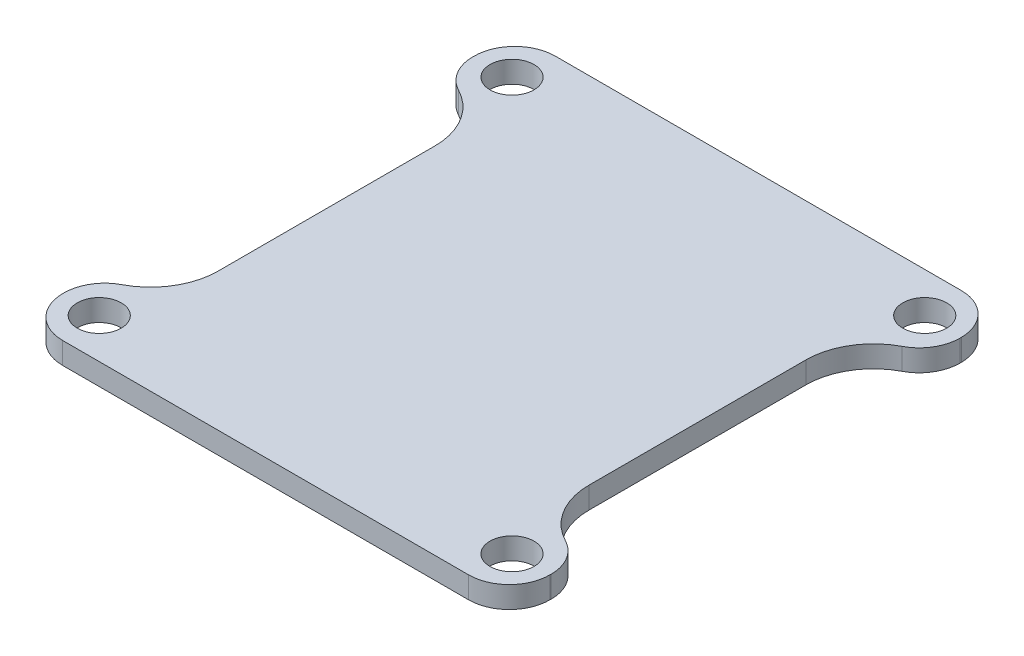
SolidWorks part; units mm, degrees
ref_plane "Front Plane" through (0, 0, 0) normal (0, 0, 1) x (1, 0, 0)
ref_plane "Top Plane" through (0, 0, 0) normal (0, 1, 0) x (1, 0, 0)
ref_plane "Right Plane" through (0, 0, 0) normal (1, 0, 0) x (0, 0, -1)
sketch "Sketch1" plane through (0, 0, 0) normal (0, 1, 0) x (1, 0, 0)
  line L0 (0, 18.2) -> (0, -18.2) construction
  line L1 (-18, 18.2) -> (18, 18.2)
  line L2 (-18, 18.2) -> (-18, -18.2)
  line L3 (-18, -18.2) -> (18, -18.2)
  line L4 (18, 18.2) -> (18, -18.2)
  line L5 (-18, 18.2) -> (18, -18.2) construction
  line L6 (-18, -18.2) -> (18, 18.2) construction
  line L7 (13.7, 18.2) -> (-13.7, 18.2)
  line L8 (13.7, 18.2) -> (13.7, -18.2)
  line L9 (13.7, -18.2) -> (-13.7, -18.2)
  line L10 (-13.7, 18.2) -> (-13.7, -18.2)
  line L11 (13.7, 18.2) -> (-13.7, -18.2) construction
  line L12 (13.7, -18.2) -> (-13.7, 18.2) construction
  line L13 (-18, 0) -> (18, 0) construction
  line L15 (18, 12.1) -> (-18, 12.1)
  line L16 (18, 12.1) -> (18, -12.1)
  line L17 (18, -12.1) -> (-18, -12.1)
  line L18 (-18, 12.1) -> (-18, -12.1)
  line L19 (18, 12.1) -> (-18, -12.1) construction
  line L20 (18, -12.1) -> (-18, 12.1) construction
  circle A0 centre (-15.25, 15.25) radius 1.625
  circle A1 centre (15.25, 15.25) radius 1.625
  circle A2 centre (15.25, -15.25) radius 1.625
  circle A3 centre (-15.25, -15.25) radius 1.625
  point P0 (0, 0)
  point P5 (0, 0)
  point P23 (0, 0)
  point P28 (0, 0)
  dimension "D4" = 3.25
  dimension "D1" = 36.4
  dimension "D2" = 36
  dimension "D3" = 27.4
  dimension "D5" = 30.5
  dimension "D6" = 30.5
  dimension "D7" = 24.2
extrude "Boss-Extrude1" add sketch "Sketch1" along normal blind 1.6 contours L15 L8 L1 L10 | L17 L8 L15 L10 | L4 L17 L8 L3 A2 | L8 L17 L10 L3 | L10 L17 L2 L3 A3 | L15 L4 L1 L8 A1 | L15 L10 L1 L2 A0
fillet "Fillet1" radius 3 8 edges at (-18, 0.8, 12.1) (-18, 0.8, -12.1) (18, 0.8, -12.1) (18, 0.8, 12.1) (18, 0.8, 18.2) (-18, 0.8, 18.2) (-18, 0.8, -18.2) (18, 0.8, -18.2)
fillet "Fillet2" radius 5 4 edges at (13.7, 0.8, -12.1) (13.7, 0.8, 12.1) (-13.7, 0.8, 12.1) (-13.7, 0.8, -12.1)
